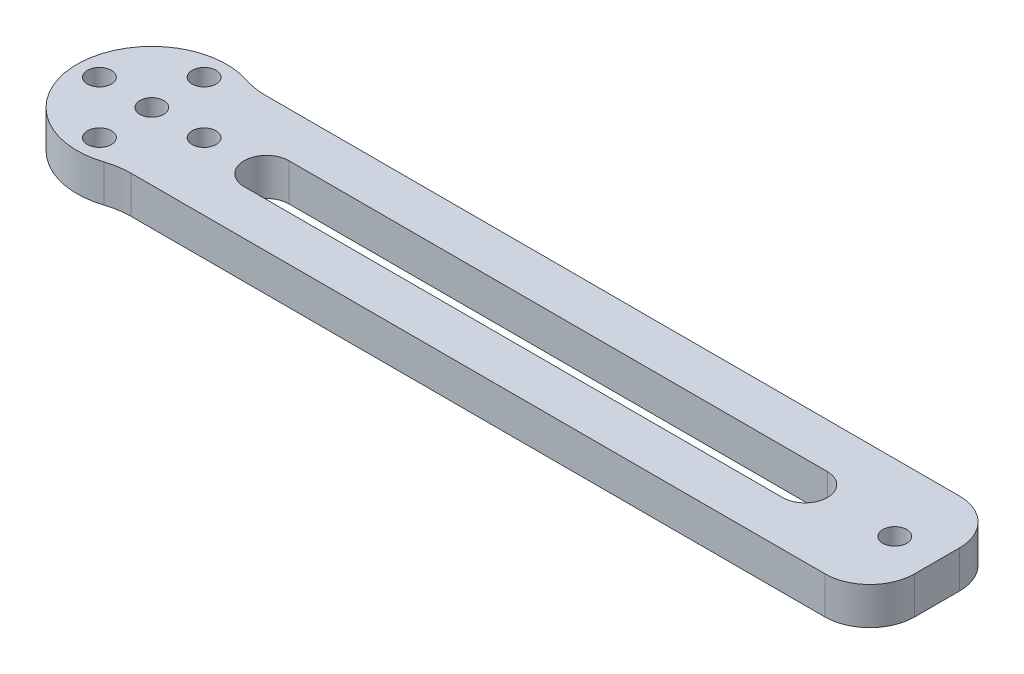
SolidWorks part; units mm, degrees
material "A-玻璃纤维"
ref_plane "前视基准面" through (0, 0, 0) normal (0, 0, 1) x (1, 0, 0)
ref_plane "上视基准面" through (0, 0, 0) normal (0, 1, 0) x (1, 0, 0)
ref_plane "右视基准面" through (0, 0, 0) normal (1, 0, 0) x (0, 0, -1)
other "Configuration Table"
sketch "草图1" plane through (0, 0, 0) normal (0, 1, 0) x (1, 0, 0)
  line L0 (-9, 0) -> (0, 0) construction
  line L1 (0, 9) -> (99, 9)
  line L2 (105, 3) -> (105, -3)
  line L3 (99, -9) -> (0, -9)
  line L4 (0, 0) -> (99.34, 0) construction
  line L5 (15.34, 0) -> (87.34, 0) construction
  line L6 (15.34, 3) -> (87.34, 3)
  line L7 (15.34, -3) -> (87.34, -3)
  circle A0 centre (0, 0) radius 1.6
  circle A1 centre (0, 0) radius 9
  circle A2 centre (0, 0) radius 7 construction
  circle A3 centre (-7, 0) radius 1.6
  circle A4 centre (0, 7) radius 1.6
  circle A5 centre (7, 0) radius 1.6
  circle A6 centre (0, -7) radius 1.6
  circle A7 centre (99.34, 0) radius 1.6
  arc A8 (105, -3) -> (99, -9) centre (99, -3) cw
  arc A9 (99, 9) -> (105, 3) centre (99, 3) cw
  arc A10 (15.34, 3) -> (15.34, -3) centre (15.34, 0) ccw
  arc A11 (87.34, -3) -> (87.34, 3) centre (87.34, 0) ccw
  point P16 (0, 0)
  point P25 (105, 9)
  point P28 (51.34, 0)
  dimension "D1" = 3.2
  dimension "D2" = 18
  dimension "D3" = 14
  dimension "D4" = 3.2
  dimension "D7" = 3.2
  dimension "D10" = 6
  dimension "D12" = 3
  dimension "D6" = 105
  dimension "D8" = 9
  dimension "D9" = 5.66
  dimension "D11" = 72
  dimension "D13" = 12
  dimension "D5" = 4
extrude "凸台-拉伸1" add sketch "草图1" along normal blind 5 contours A9 L1 A1 L3 A8 L2 A11 L7 A10 L6 A7 | A1 A6 A5 A4 A3 A0
sketch "草图2" plane through (0, 0, 0) normal (0, -1, 0) x (1, 0, 0)
  circle A0 centre (99.34, 0) radius 4.2
  dimension "D1" = 8.4
extrude "切除-拉伸1" cut sketch "草图2" against normal blind 2.5
sketch "草图3" plane through (0, 5, 0) normal (0, 1, 0) x (1, 0, 0)
  circle A0 centre (0, 0) radius 9
  circle A1 centre (0, 0) radius 10
  dimension "D1" = 18
  dimension "D2" = 20
extrude "凸台-拉伸2" add sketch "草图3" against normal blind 5
fillet "圆角1" radius 10 2 edges at (4.3589, 2.5, 9) (4.3589, 2.5, -9)
